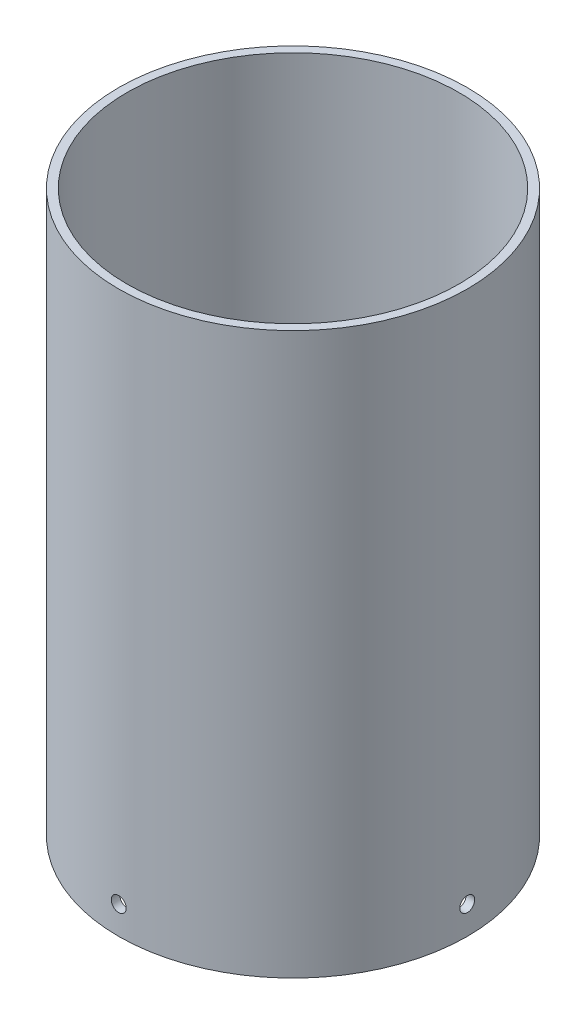
SolidWorks part; units mm, degrees
material "7075-T6 (SN)"
ref_plane "Ön Düzlem" through (0, 0, 0) normal (0, 0, 1) x (1, 0, 0)
ref_plane "Üst Düzlem" through (0, 0, 0) normal (0, 1, 0) x (1, 0, 0)
ref_plane "Sağ Düzlem" through (0, 0, 0) normal (1, 0, 0) x (0, 0, -1)
sketch "Çizim1" plane through (0, 0, 0) normal (0, 1, 0) x (1, 0, 0)
  circle A0 centre (0, 0) radius 62.2
  circle A1 centre (0, 0) radius 59.2
  dimension "D1" = 124.4
  dimension "D2" = 118.4
extrude "Yükseklik-Ekstrüzyon1" add sketch "Çizim1" along normal mid plane 200
sketch "Çizim4" plane through (0, -100, 0) normal (0, -1, 0) x (1, 0, 0)
  line L0 (0, 0) -> (62.2, 0) construction
  line L1 (62.2, 24.0714) -> (62.2, -24.0714) construction
  circle A0 centre (0, 0) radius 62.2 construction
  point P9 (62.2, 0)
sketch "Çizim5" plane through (0, 100, 0) normal (0, 1, 0) x (1, 0, 0)
  line L0 (0, 0) -> (62.2, 0) construction
  line L1 (62.2, -24.0714) -> (62.2, 24.0714) construction
ref_plane "Düzlem1" through (62.2, 0, 0) normal (-1, 0, 0) x (0, 0, 1)
sketch "Çizim8" plane through (62.2, 0, 0) normal (-1, 0, 0) x (0, 0, 1)
  line L0 (0, -100) -> (0, -90) construction
  point P1 (0, -90)
  point P7 (0, -90)
  dimension "D1" = 10
hole_wizard "M5 Boşluklu Delik1" positions "Çizim8" profile "Çizim10" hole size "M5" standard "ISO"
sketch "Çizim10" plane through (62.2, -90, 0) normal (0, 1, 0) x (0, 0, -1)
  line L0 (0, 0) -> (0, 10.2923)
  line L1 (0, 10.2923) -> (2.65, 8.7)
  line L2 (2.65, 8.7) -> (2.65, 0)
  line L5 (2.65, 0) -> (0, 0)
  line L10 (0, 10.2923) -> (-2.65, 8.7) construction
  line L11 (0, -6.35) -> (0, 107.95) construction
  dimension "Hole Dia." = 5.3
  dimension "Hole Depth" = 8.7
  dimension "Drill Angle" = 118
pattern_circular "Dairesel Kaplama1" count 4 over 360 about axis through (0, -100, 0) along (0, 1, 0) of "M5 Boşluklu Delik1"
